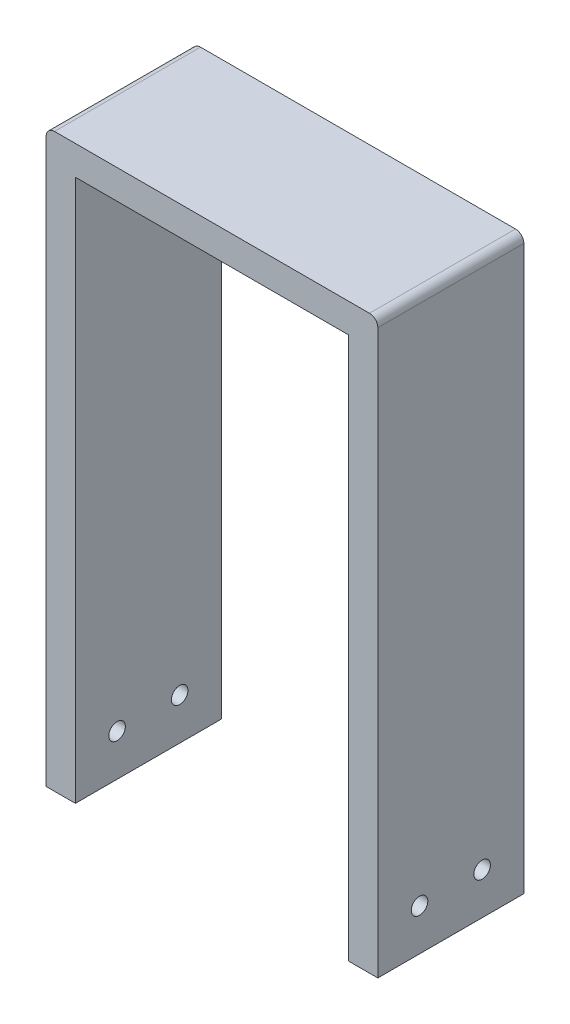
SolidWorks part; units mm, degrees
ref_plane "Front Plane" through (0, 0, 0) normal (0, 0, 1) x (1, 0, 0)
ref_plane "Top Plane" through (0, 0, 0) normal (0, 1, 0) x (1, 0, 0)
ref_plane "Right Plane" through (0, 0, 0) normal (1, 0, 0) x (0, 0, -1)
other "Configuration Table"
sketch "Sketch1" plane through (0, 0, 0) normal (0, 0, 1) x (1, 0, 0)
  line L0 (-39.75, -65) -> (-39.75, 72)
  line L2 (32.75, -65) -> (32.75, 65)
  line L3 (32.75, 65) -> (-32.75, 65)
  line L4 (-32.75, -65) -> (-32.75, 65)
  line L5 (32.75, -65) -> (-32.75, 65) construction
  line L6 (32.75, 65) -> (-32.75, -65) construction
  line L7 (39.75, 72) -> (-39.75, 72)
  line L8 (39.75, -65) -> (39.75, 72)
  line L9 (-39.75, -65) -> (-32.75, -65)
  line L10 (32.75, -65) -> (39.75, -65)
  point P0 (0, 0)
  dimension "D1" = 65.5
  dimension "D2" = 130
  dimension "D3" = 7
extrude "Boss-Extrude1" add sketch "Sketch1" along normal mid plane 35
sketch "Sketch2" plane through (0, 0, 0) normal (1, 0, 0) x (0, 0, -1)
  line L0 (-7.5, -55) -> (7.5, -55) construction
  line L1 (-17.5, -65) -> (17.5, -65) construction
  circle A0 centre (-7.5, -55) radius 1.985
  circle A1 centre (7.5, -55) radius 1.985
  point P4 (0, -55)
  dimension "D3" = 3.97
  dimension "D1" = 15
  dimension "D2" = 10
extrude "Cut-Extrude1" cut sketch "Sketch2" against normal through all both and the other way through all
fillet "Fillet1" radius 2 2 edges at (-39.75, 72, 0) (39.75, 72, 0)
